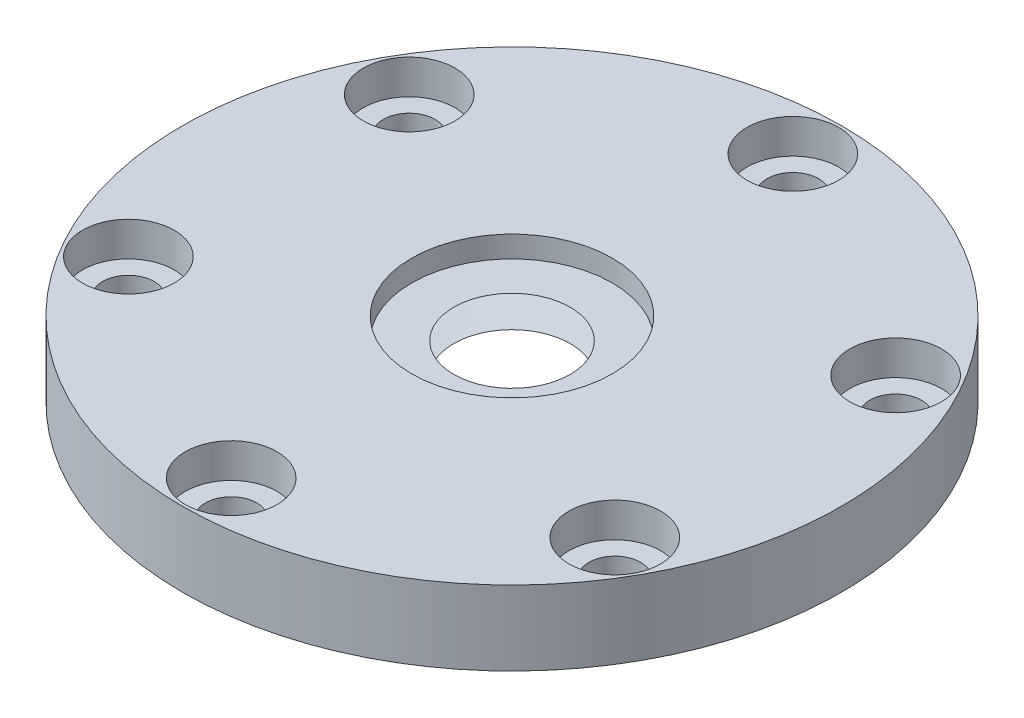
SolidWorks part; units mm, degrees
ref_plane "前视基准面" through (0, 0, 0) normal (0, 0, 1) x (1, 0, 0)
ref_plane "上视基准面" through (0, 0, 0) normal (0, 1, 0) x (1, 0, 0)
ref_plane "右视基准面" through (0, 0, 0) normal (1, 0, 0) x (0, 0, -1)
other "Configuration Table"
sketch "草图1" plane through (0, 0, 0) normal (0, 1, 0) x (1, 0, 0)
  circle A0 centre (0, 0) radius 57.5
  dimension "D1" = 115
extrude "凸台-拉伸1" add sketch "草图1" along normal mid plane 13
sketch "草图3" plane through (0, 6.5, 0) normal (0, 1, 0) x (1, 0, 0)
  circle A0 centre (0, 0) radius 49 construction
  circle A1 centre (0, 49) radius 8
  dimension "D1" = 98
  dimension "D2" = 16
extrude "切除-拉伸1" cut sketch "草图3" against normal blind 6
sketch "草图4" plane through (0, 0.5, 0) normal (0, 1, 0) x (1, 0, 0)
  circle A0 centre (0, 49) radius 4.5
  circle A1 centre (0, 49) radius 8 construction
  dimension "D1" = 9
extrude "切除-拉伸2" cut sketch "草图4" against normal through all
sketch "草图5" plane through (0, 0, 0) normal (0, 0, 1) x (1, 0, 0)
  line L0 (0, 37.6643) -> (0, -26.8855) construction
pattern_circular "阵列(圆周)1" count 6 over 360 about axis through (0, 0, 0) along (0, 1, 0) of "切除-拉伸2", "切除-拉伸1"
sketch "草图6" plane through (0, 6.5, 0) normal (0, 1, 0) x (1, 0, 0)
  circle A0 centre (0, 0) radius 17.5
  dimension "D1" = 35
extrude "切除-拉伸3" cut sketch "草图6" against normal blind 3.75
sketch "草图8" plane through (0, 0, 0) normal (0, 0, 1) x (1, 0, 0)
  line L0 (-10.158, 2.75) -> (-18.1894, 2)
  line L1 (-18.1894, 2) -> (-18.1894, -2)
  line L2 (-18.1894, -2) -> (-10.158, -2.75)
  line L3 (-10.158, -2.75) -> (0, -2.75)
  line L4 (0, 37.6643) -> (0, -26.8855) construction
  line L5 (0, -2.75) -> (0, 2.75)
  line L6 (0, 2.75) -> (-10.158, 2.75)
  line L7 (-18.1894, 0) -> (16.5296, 0) construction
  dimension "D1" = 3.75
  dimension "D2" = 4
  dimension "D3" = 5.5
revolve "切除-旋转1" cut sketch "草图8" angle 360 about L0
sketch "草图9" plane through (0, -2.75, 0) normal (0, 1, 0) x (1, 0, 0)
  circle A0 centre (0, 0) radius 17.5
extrude "切除-拉伸4" cut sketch "草图9" against normal blind 3.75
sketch "草图10" plane through (0, -6.5, 0) normal (0, -1, 0) x (1, 0, 0)
  circle A0 centre (0, 0) radius 34
  circle A1 centre (0, 0) radius 40
  dimension "D1" = 68
  dimension "D2" = 80
extrude "凸台-拉伸2" add sketch "草图10" along normal blind 5
